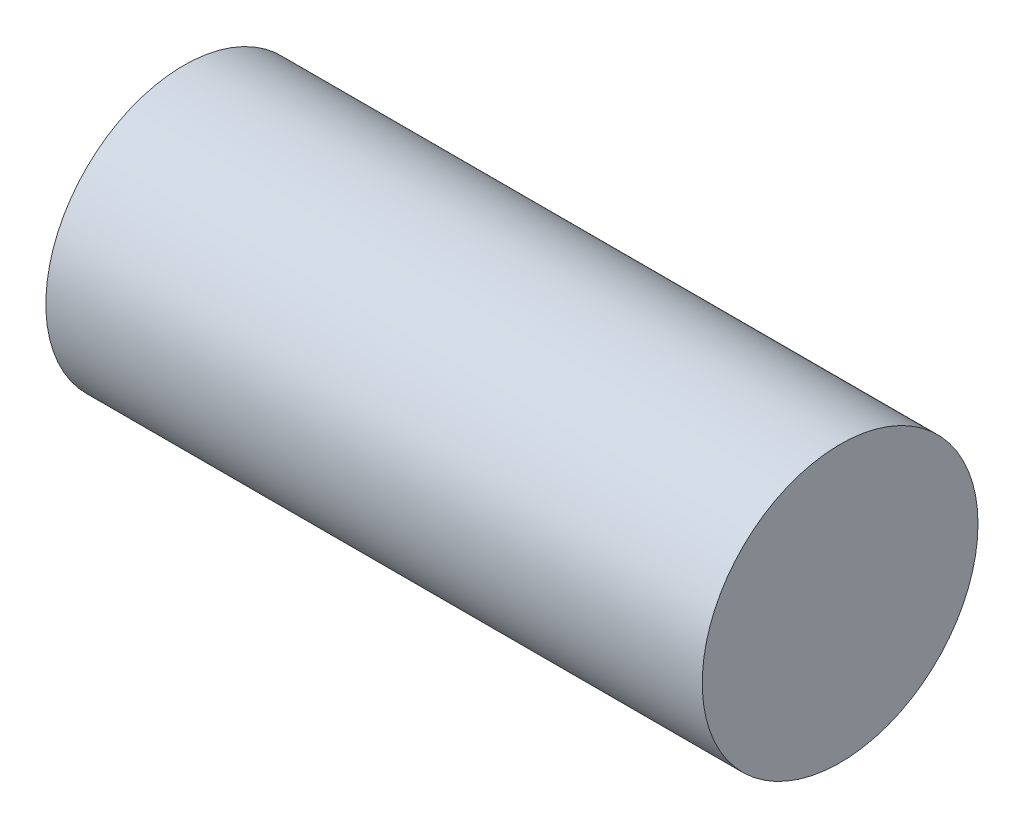
SolidWorks part; units mm, degrees
ref_plane "Front Plane" through (0, 0, 0) normal (0, 0, 1) x (1, 0, 0)
ref_plane "Top Plane" through (0, 0, 0) normal (0, 1, 0) x (1, 0, 0)
ref_plane "Right Plane" through (0, 0, 0) normal (1, 0, 0) x (0, 0, -1)
sketch "Sketch1" plane through (0, 0, 0) normal (1, 0, 0) x (0, 0, -1)
  circle A0 centre (275.621, 106.806) radius 8.0999
  point P2 (267.6208, 105.539)
extrude "Boss-Extrude1" add sketch "Sketch1" against normal blind 38.5582
